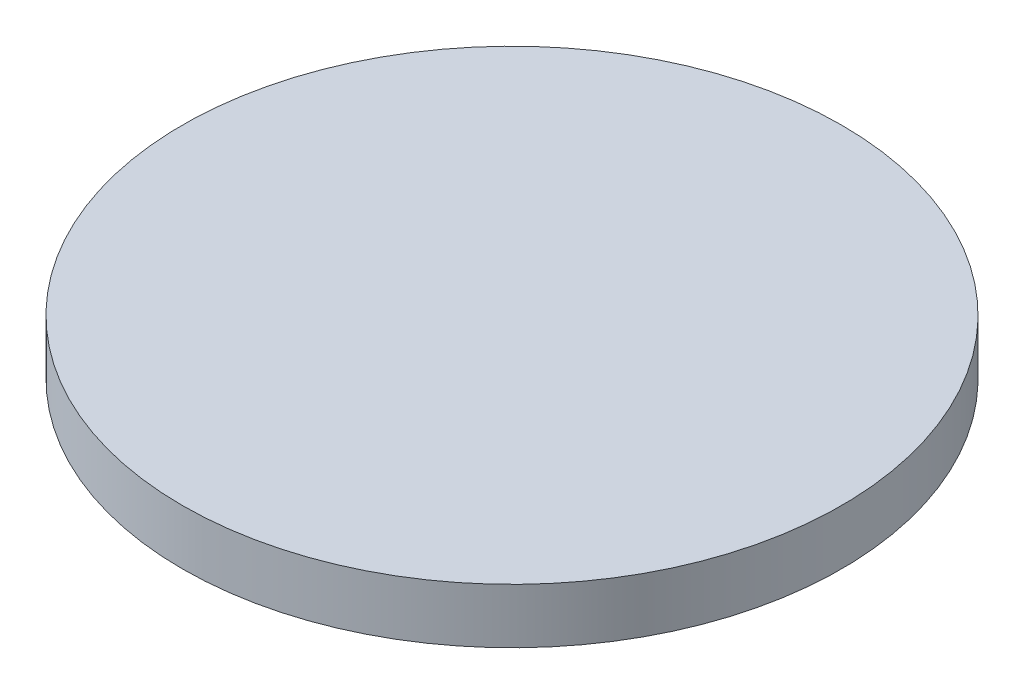
SolidWorks part; units mm, degrees
ref_plane "Front Plane" through (0, 0, 0) normal (0, 0, 1) x (1, 0, 0)
ref_plane "Top Plane" through (0, 0, 0) normal (0, 1, 0) x (1, 0, 0)
ref_plane "Right Plane" through (0, 0, 0) normal (1, 0, 0) x (0, 0, -1)
sketch "Sketch1" plane through (0, 0, 0) normal (0, 1, 0) x (1, 0, 0)
  circle A0 centre (0, 0) radius 30
  dimension "D1" = 60
extrude "Boss-Extrude1" add sketch "Sketch1" along normal blind 5
